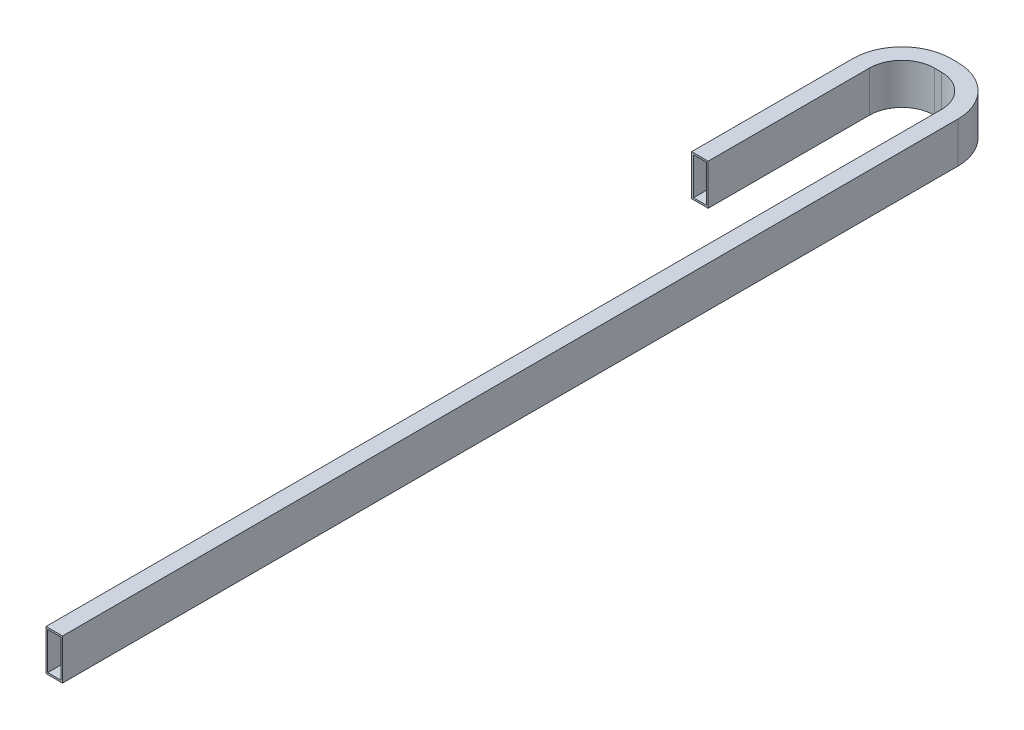
SolidWorks part; units mm, degrees
ref_plane "Front" through (0, 0, 0) normal (0, 0, 1) x (1, 0, 0)
ref_plane "Top" through (0, 0, 0) normal (0, 1, 0) x (1, 0, 0)
ref_plane "Right" through (0, 0, 0) normal (1, 0, 0) x (0, 0, -1)
sketch "Sketch1" plane through (0, 0, 0) normal (0, 0, 1) x (1, 0, 0)
  line L0 (6.35, 107.95) -> (6.35, 0) construction
  line L1 (6.35, 106.934) -> (21.336, 106.934)
  line L2 (6.35, 106.934) -> (6.35, 69.85)
  line L3 (6.35, 69.85) -> (21.336, 69.85)
  line L4 (21.336, 106.934) -> (21.336, 69.85)
  line L5 (79.375, 63.5) -> (98.425, 63.5) construction
  line L6 (7.9375, 105.3465) -> (19.7485, 105.3465)
  line L7 (19.7485, 105.3465) -> (19.7485, 71.4375)
  line L8 (7.9375, 71.4375) -> (19.7485, 71.4375)
  line L9 (7.9375, 105.3465) -> (7.9375, 71.4375)
  dimension "D1" = 14.986
  dimension "D2" = 37.084
  dimension "D3" = 6.35
  dimension "D4" = 1.5875
extrude "Extrude1" add sketch "Sketch1" against normal blind 12.7
ref_plane "Plane1" through (0, 0, 666.75) normal (0, 0, 1) x (1, 0, 0)
sketch "Sketch2" plane through (0, 0, 666.75) normal (0, 0, 1) x (1, 0, 0)
  line L0 (21.336, 106.934) -> (6.35, 106.934) construction
  line L1 (101.6, 69.85) -> (86.614, 69.85)
  line L2 (101.6, 69.85) -> (101.6, 106.934)
  line L3 (101.6, 106.934) -> (86.614, 106.934)
  line L4 (86.614, 69.85) -> (86.614, 106.934)
  line L5 (6.35, 69.85) -> (21.336, 69.85) construction
  line L6 (101.6, 111.125) -> (101.6, 66.675) construction
  line L7 (100.0125, 71.4375) -> (88.2015, 71.4375)
  line L8 (88.2015, 71.4375) -> (88.2015, 105.3465)
  line L9 (100.0125, 105.3465) -> (88.2015, 105.3465)
  line L10 (100.0125, 71.4375) -> (100.0125, 105.3465)
  dimension "D1" = 1.5875
extrude "Extrude2" add sketch "Sketch2" against normal blind 12.7
sketch3d "3DSketch1"
  line L0 (101.6, 69.85, 654.05) -> (101.6, 69.85, -146.5138)
  line L1 (57.15, 69.85, -190.9638) -> (50.8, 69.85, -190.9638)
  line L2 (6.35, 69.85, -146.5138) -> (6.35, 69.85, -12.7)
  line L3 (6.35, 69.85, -12.7) -> (6.35, 69.85, 0) construction
  arc A0 (6.35, 69.85, -146.5138) -> (50.8, 69.85, -190.9638) centre (50.8, 69.85, -146.5138) ccw
  arc A1 (101.6, 69.85, -146.5138) -> (57.15, 69.85, -190.9638) centre (57.15, 69.85, -146.5138) ccw
  point P10 (6.35, 69.85, -190.9638)
  point P11 (50.8, 25.4, -146.5138)
  point P14 (101.6, 69.85, -190.9638)
  point P15 (57.15, 114.3, -146.5138)
  dimension "D1" = 44.45
sketch "Sketch3" plane through (0, 0, 654.05) normal (0, 0, -1) x (-1, 0, 0)
  line L4 (-101.6, 106.934) -> (-101.6, 69.85)
  line L5 (-101.6, 69.85) -> (-86.614, 69.85)
  line L6 (-86.614, 69.85) -> (-86.614, 106.934)
  line L7 (-86.614, 106.934) -> (-101.6, 106.934)
  line L8 (-86.614, 69.85) -> (-101.6, 69.85)
  line L9 (-86.614, 69.85) -> (-101.6, 69.85) construction
  line L10 (-86.614, 69.85) -> (-86.614, 106.934)
  line L11 (-86.614, 106.934) -> (-101.6, 106.934)
  line L12 (-101.6, 106.934) -> (-101.6, 69.85)
  line L13 (-101.6, 69.85) -> (-101.6, 106.934) construction
  line L16 (-100.0125, 71.4375) -> (-88.2015, 71.4375)
  line L17 (-100.0125, 105.3465) -> (-100.0125, 71.4375)
  line L18 (-88.2015, 105.3465) -> (-100.0125, 105.3465)
  line L19 (-88.2015, 71.4375) -> (-88.2015, 105.3465)
  line L20 (-100.0125, 71.4375) -> (-88.2015, 71.4375)
  line L21 (-100.0125, 105.3465) -> (-100.0125, 71.4375)
  line L22 (-88.2015, 105.3465) -> (-100.0125, 105.3465)
  line L23 (-88.2015, 71.4375) -> (-88.2015, 105.3465)
  dimension "D1" = 0
  dimension "D2" = 0
sweep "Sweep1" add profiles "Sketch3" path "3DSketch1"
